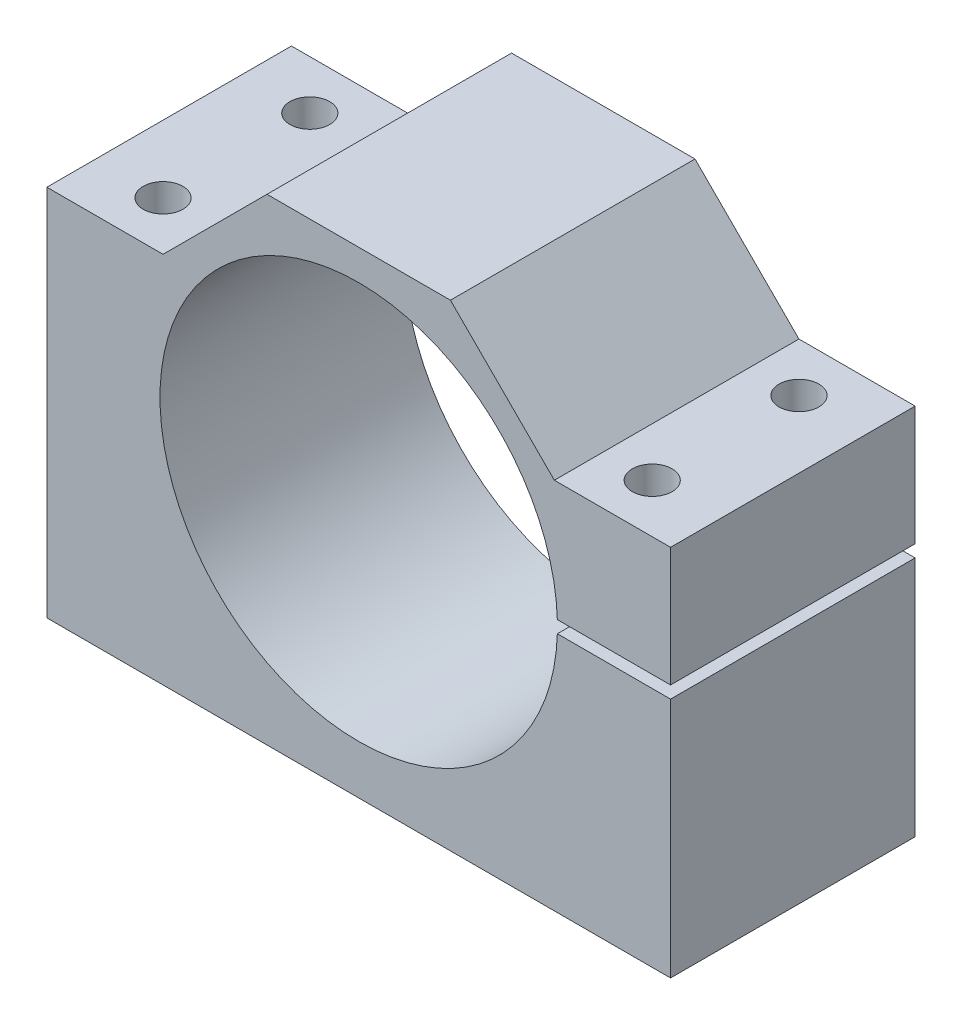
SolidWorks part; units mm, degrees
ref_plane "前视基准面" through (0, 0, 0) normal (0, 0, 1) x (1, 0, 0)
ref_plane "上视基准面" through (0, 0, 0) normal (0, 1, 0) x (1, 0, 0)
ref_plane "右视基准面" through (0, 0, 0) normal (1, 0, 0) x (0, 0, -1)
other "Configuration Table"
sketch "草图1" plane through (0, 0, 0) normal (0, 0, 1) x (1, 0, 0)
  line L0 (0, 61) -> (19, 61)
  line L1 (0, 0) -> (102, 0)
  line L2 (0, 0) -> (0, 61)
  line L3 (36, 78) -> (66, 78)
  line L4 (102, 0) -> (102, 39.5)
  line L5 (19, 61) -> (36, 78)
  line L6 (66, 78) -> (83, 61)
  line L7 (83, 61) -> (102, 61)
  line L8 (51, 0) -> (51, 81.2977) construction
  line L9 (83.4846, 41.5) -> (102, 41.5)
  line L10 (102, 39.5) -> (83.4846, 39.5)
  line L11 (51, 40.5) -> (76.3563, 40.5) construction
  line L12 (102, 41.5) -> (102, 61)
  arc A0 (83.4846, 41.5) -> (83.4846, 39.5) centre (51, 40.5) ccw
  point P13 (83.4846, 41.5)
  point P17 (0, 0)
  point P19 (102, 40.5)
  point P21 (83.7733, 41.5)
  dimension "D7" = 65
  dimension "D1" = 30
  dimension "D2" = 61
  dimension "D3" = 78
  dimension "D4" = 64
  dimension "D5" = 102
  dimension "D6" = 37.5
  dimension "D8" = 2
extrude "凸台-拉伸1" add sketch "草图1" along normal blind 40
sketch "草图2" plane through (0, 61, 0) normal (0, 1, 0) x (1, 0, 0)
  line L0 (51, 0) -> (51, -27.6) construction
  line L1 (66, 0) -> (36, 0) construction
  line L2 (0, -20) -> (70.6555, -20) construction
  line L3 (0, -40) -> (0, 0) construction
  circle A0 centre (11, -8) radius 3.25
  circle A1 centre (11, -32) radius 3.25
  circle A2 centre (91, -8) radius 3.25
  circle A3 centre (91, -32) radius 3.25
  point P16 (11.0103, -8.3034)
  dimension "D1" = 6.5
  dimension "D2" = 6.5
  dimension "D3" = 24
  dimension "D4" = 80
  dimension "D5" = 80
extrude "切除-拉伸1" cut sketch "草图2" against normal through all
